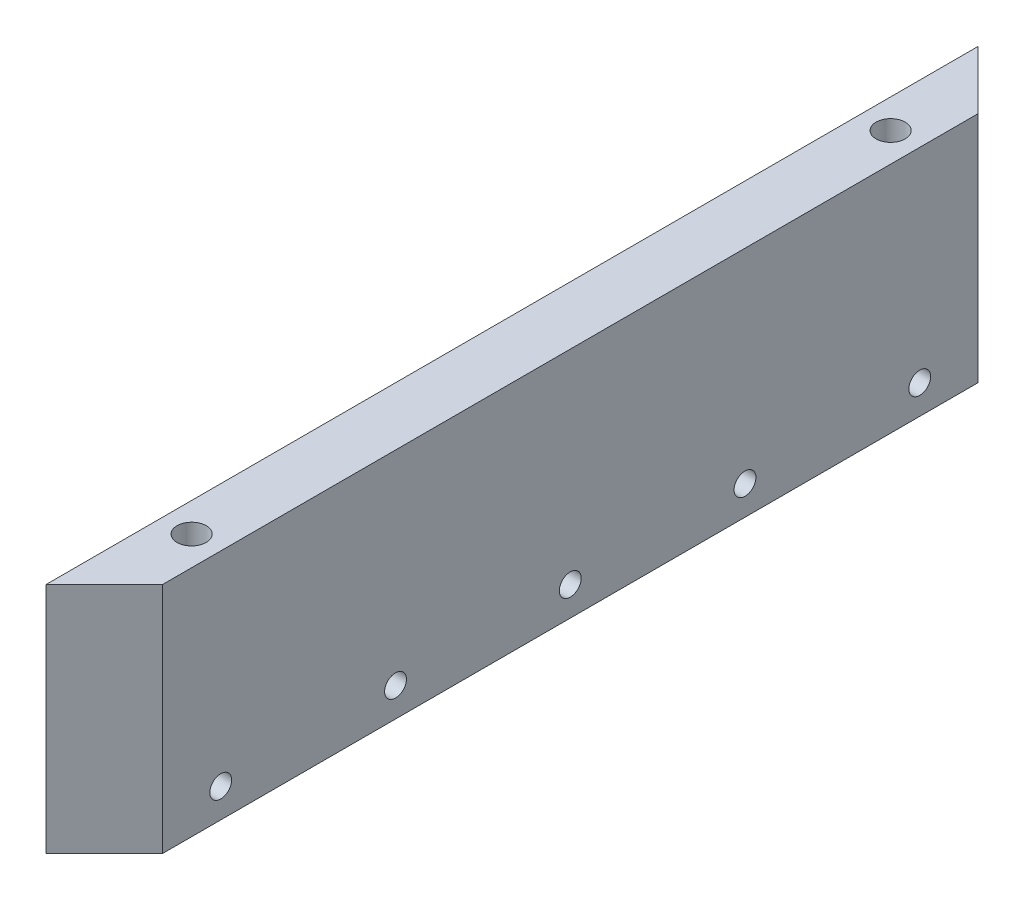
SolidWorks part; units mm, degrees
material "Mahogany"
ref_plane "Front Plane" through (0, 0, 0) normal (0, 0, 1) x (1, 0, 0)
ref_plane "Top Plane" through (0, 0, 0) normal (0, 1, 0) x (1, 0, 0)
ref_plane "Right Plane" through (0, 0, 0) normal (1, 0, 0) x (0, 0, -1)
sketch "Sketch1" plane through (0, 0, 0) normal (1, 0, 0) x (0, 0, -1)
  line L1 (-101.6, 25.4) -> (101.6, 25.4)
  line L2 (-101.6, 25.4) -> (-101.6, -25.4)
  line L3 (-101.6, -25.4) -> (101.6, -25.4)
  line L4 (101.6, 25.4) -> (101.6, -25.4)
  line L5 (-101.6, 25.4) -> (101.6, -25.4) construction
  line L6 (-101.6, -25.4) -> (101.6, 25.4) construction
  point P0 (0, 0)
  dimension "D1" = 203.2
  dimension "D2" = 50.8
extrude "Boss-Extrude1" add sketch "Sketch1" along normal blind 12.7
sketch "Sketch2" plane through (0, 25.4, 0) normal (0, 1, 0) x (1, 0, 0)
  line L0 (0, 101.6) -> (12.7, 88.9)
  line L1 (12.7, 101.6) -> (12.7, -101.6) construction
  line L2 (12.7, 88.9) -> (12.7, 101.6)
  line L3 (12.7, 101.6) -> (0, 101.6)
  line L4 (0, -101.6) -> (12.7, -88.9)
  line L5 (12.7, -88.9) -> (12.7, -101.6)
  line L6 (12.7, -101.6) -> (0, -101.6)
extrude "Cut-Extrude1" cut sketch "Sketch2" against normal through all
sketch "Sketch3" plane through (0, 25.4, 0) normal (0, 1, 0) x (1, 0, 0)
  line L0 (0, 97.1099) -> (2.2451, 99.3549)
  line L1 (0, 101.6) -> (0, -101.6) construction
  line L2 (0, 101.6) -> (12.7, 88.9) construction
  line L3 (2.2451, 99.3549) -> (0, 101.6)
  line L4 (0, 101.6) -> (0, 97.1099)
  line L5 (0, -97.1099) -> (2.2451, -99.3549)
  line L6 (12.7, -88.9) -> (0, -101.6) construction
  line L7 (2.2451, -99.3549) -> (0, -101.6)
  line L8 (0, -101.6) -> (0, -97.1099)
  dimension "D1" = 3.175
extrude "Cut-Extrude2" [suppressed] cut sketch "Sketch3" against normal through all
sketch "Sketch4" plane through (0, 0, 0) normal (-1, 0, 0) x (0, 0, 1)
  line L0 (101.6, -25.4) -> (-101.6, -25.4) construction
  line L1 (-101.6, -995.2026) -> (-101.6, 49004.7974) construction
  circle A0 centre (-76.2, -19.05) radius 2.3813
  dimension "D1" = 4.7625
  dimension "D2" = 6.35
  dimension "D3" = 101.6
  dimension "D4" = 25.4
extrude "Cut-Extrude3" cut sketch "Sketch4" against normal through all
pattern_linear "LPattern1" count 5 spacing 38.1 along (0, 0, 1) of "Cut-Extrude3"
sketch "Sketch5" plane through (0, 25.4, 0) normal (0, 1, 0) x (1, 0, 0)
  line L0 (0, 101.6) -> (0, -101.6) construction
  line L1 (6.35, 76.2) -> (0, 0) construction
  line L2 (0, 0) -> (6.35, -76.2) construction
  circle A0 centre (6.35, 76.2) radius 3.175
  circle A1 centre (6.35, -76.2) radius 3.175
  dimension "D2" = 6.35
  dimension "D1" = 6.35
  dimension "D3" = 152.4
extrude "Cut-Extrude4" cut sketch "Sketch5" against normal blind 12.7
